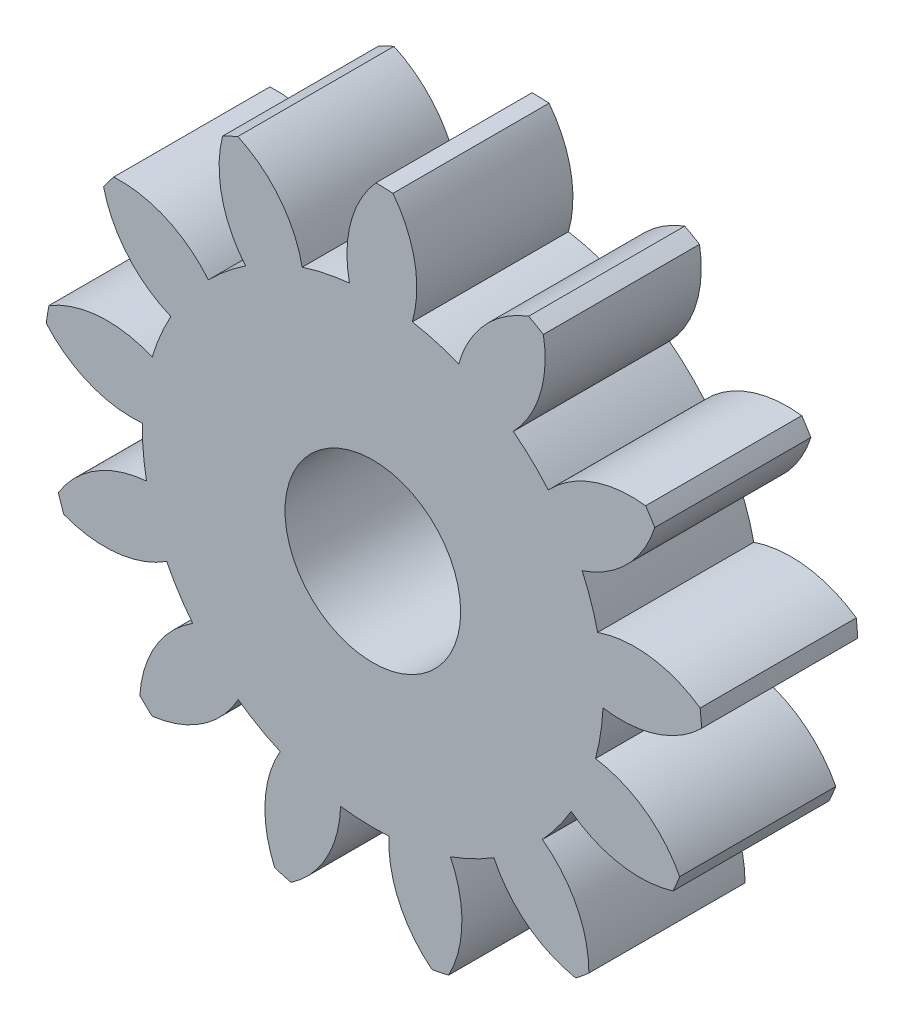
SolidWorks part; units mm, degrees
ref_plane "Front Plane" through (0, 0, 0) normal (0, 0, 1) x (1, 0, 0)
ref_plane "Top Plane" through (0, 0, 0) normal (0, 1, 0) x (1, 0, 0)
ref_plane "Right Plane" through (0, 0, 0) normal (1, 0, 0) x (0, 0, -1)
sketch "Sketch1" plane through (0, 0, 0) normal (0, 0, 1) x (1, 0, 0)
  circle A0 centre (0, 0) radius 2.25
  circle A1 centre (0, 0) radius 9.5
  dimension "D1" = 4.5
  dimension "D2" = 19
extrude "Boss-Extrude1" add sketch "Sketch1" along normal blind 4
sketch "Sketch2" plane through (0, 0, 4) normal (0, 0, 1) x (1, 0, 0)
  circle A0 centre (0, 0) radius 9.5 construction
  circle A1 centre (0, 0) radius 9.5
  arc A52 (5.3624, 2.4732) -> (7.2234, 4.3606) centre (4.4361, 5.2477) ccw
  arc A53 (7.2234, 4.3606) -> (6.9888, 4.7273) centre (0, 0) ccw
  arc A54 (6.9888, 4.7273) -> (4.4948, 3.8299) centre (6.6247, 1.8251) ccw
  arc A55 (4.4948, 3.8299) -> (3.5988, 4.682) centre (0, 0) ccw
  arc A56 (3.5988, 4.682) -> (4.3695, 7.218) centre (1.4893, 6.7082) ccw
  arc A57 (4.3695, 7.218) -> (3.9914, 7.4337) centre (0, 0) ccw
  arc A58 (3.9914, 7.4337) -> (2.2001, 5.4801) centre (5.0177, 4.6947) ccw
  arc A59 (2.2001, 5.4801) -> (1.0108, 5.8181) centre (0, 0) ccw
  arc A60 (1.0108, 5.8181) -> (0.5147, 8.4218) centre (-1.7988, 6.6319) ccw
  arc A61 (0.5147, 8.4218) -> (0.0796, 8.4371) centre (0, 0) ccw
  arc A62 (0.0796, 8.4371) -> (-0.5986, 5.8748) centre (2.2612, 6.4888) ccw
  arc A63 (-0.5986, 5.8748) -> (-1.8088, 5.6214) centre (0, 0) ccw
  arc A64 (-1.8088, 5.6214) -> (-3.4581, 7.6963) centre (-4.6747, 5.0363) ccw
  arc A65 (-3.4581, 7.6963) -> (-3.8505, 7.5077) centre (0, 0) ccw
  arc A66 (-3.8505, 7.5077) -> (-3.2602, 4.9237) centre (-1.0133, 6.7964) ccw
  arc A67 (-3.2602, 4.9237) -> (-4.214, 4.1369) centre (0, 0) ccw
  arc A68 (-4.214, 4.1369) -> (-6.6386, 5.2077) centre (-6.4798, 2.287) ccw
  arc A69 (-6.6386, 5.2077) -> (-6.8984, 4.8583) centre (0, 0) ccw
  arc A70 (-6.8984, 4.8583) -> (-5.1749, 2.8446) centre (-4.0556, 5.547) ccw
  arc A71 (-5.1749, 2.8446) -> (-5.6539, 1.7047) centre (0, 0) ccw
  arc A72 (-5.6539, 1.7047) -> (-8.2983, 1.526) centre (-6.8004, -0.9863) ccw
  arc A73 (-8.2983, 1.526) -> (-8.366, 1.096) centre (0, 0) ccw
  arc A74 (-8.366, 1.096) -> (-5.9042, 0.1139) centre (-6.1689, 3.0269) ccw
  arc A75 (-5.9042, 0.1139) -> (-5.7984, -1.1181) centre (0, 0) ccw
  arc A76 (-5.7984, -1.1181) -> (-8.057, -2.5052) centre (-5.5631, -4.0336) ccw
  arc A77 (-8.057, -2.5052) -> (-7.9171, -2.9174) centre (0, 0) ccw
  arc A78 (-7.9171, -2.9174) -> (-5.2808, -2.6429) centre (-6.869, -0.1867) ccw
  arc A79 (-5.2808, -2.6429) -> (-4.6147, -3.6847) centre (0, 0) ccw
  arc A80 (-4.6147, -3.6847) -> (-5.9699, -5.9625) centre (-3.0514, -6.1568) ccw
  arc A81 (-5.9699, -5.9625) -> (-5.6544, -6.2625) centre (0, 0) ccw
  arc A82 (-5.6544, -6.2625) -> (-3.4477, -4.7943) centre (-5.9954, -3.3574) ccw
  arc A83 (-3.4477, -4.7943) -> (-2.3737, -5.4072) centre (0, 0) ccw
  arc A84 (-2.3737, -5.4072) -> (-2.5152, -8.0539) centre (0.1594, -6.8697) ccw
  arc A85 (-2.5152, -8.0539) -> (-2.0964, -8.1729) centre (0, 0) ccw
  arc A86 (-2.0964, -8.1729) -> (-0.8247, -5.8474) centre (-3.7484, -5.7591) ccw
  arc A87 (-0.8247, -5.8474) -> (0.411, -5.8909) centre (0, 0) ccw
  arc A88 (0.411, -5.8909) -> (1.5158, -8.3002) centre (3.3336, -6.0087) ccw
  arc A89 (1.5158, -8.3002) -> (1.9419, -8.211) centre (0, 0) ccw
  arc A90 (1.9419, -8.211) -> (1.9871, -5.5609) centre (-0.6427, -6.8414) ccw
  arc A91 (1.9871, -5.5609) -> (3.1016, -5.0252) centre (0, 0) ccw
  arc A92 (3.1016, -5.0252) -> (5.1995, -6.6451) centre (5.7441, -3.7712) ccw
  arc A93 (5.1995, -6.6451) -> (5.5353, -6.3681) centre (0, 0) ccw
  arc A94 (5.5353, -6.3681) -> (4.3438, -4.0004) centre (2.6103, -6.3564) ccw
  arc A95 (4.3438, -4.0004) -> (5.0816, -3.0082) centre (0, 0) ccw
  arc A96 (5.0816, -3.0082) -> (7.692, -3.4676) centre (6.8388, -0.6698) ccw
  arc A97 (7.692, -3.4676) -> (7.8606, -3.0663) centre (0, 0) ccw
  arc A98 (7.8606, -3.0663) -> (5.7053, -1.5235) centre (5.2653, -4.4153) ccw
  arc A99 (5.7053, -1.5235) -> (5.8975, -0.3021) centre (0, 0) ccw
  arc A100 (5.8975, -0.3021) -> (8.4224, 0.5042) centre (6.3667, 2.585) ccw
  arc A101 (8.4224, 0.5042) -> (8.3852, 0.938) centre (0, 0) ccw
  arc A102 (8.3852, 0.938) -> (5.7598, 1.3024) centre (6.714, -1.4626) ccw
  arc A103 (5.7598, 1.3024) -> (5.3624, 2.4732) centre (0, 0) ccw
  arc A104 (5.3624, 2.4732) -> (7.2234, 4.3606) centre (4.4361, 5.2477) ccw
  arc A105 (7.2234, 4.3606) -> (6.9888, 4.7273) centre (0, 0) ccw
  arc A106 (6.9888, 4.7273) -> (4.4948, 3.8299) centre (6.6247, 1.8251) ccw
  arc A107 (4.4948, 3.8299) -> (3.5988, 4.682) centre (0, 0) ccw
  arc A108 (3.5988, 4.682) -> (4.3695, 7.218) centre (1.4893, 6.7082) ccw
  arc A109 (4.3695, 7.218) -> (3.9914, 7.4337) centre (0, 0) ccw
  arc A110 (3.9914, 7.4337) -> (2.2001, 5.4801) centre (5.0177, 4.6947) ccw
  arc A111 (2.2001, 5.4801) -> (1.0108, 5.8181) centre (0, 0) ccw
  arc A112 (1.0108, 5.8181) -> (0.5147, 8.4218) centre (-1.7988, 6.6319) ccw
  arc A113 (0.5147, 8.4218) -> (0.0796, 8.4371) centre (0, 0) ccw
  arc A114 (0.0796, 8.4371) -> (-0.5986, 5.8748) centre (2.2612, 6.4888) ccw
  arc A115 (-0.5986, 5.8748) -> (-1.8088, 5.6214) centre (0, 0) ccw
  arc A116 (-1.8088, 5.6214) -> (-3.4581, 7.6963) centre (-4.6747, 5.0363) ccw
  arc A117 (-3.4581, 7.6963) -> (-3.8505, 7.5077) centre (0, 0) ccw
  arc A118 (-3.8505, 7.5077) -> (-3.2602, 4.9237) centre (-1.0133, 6.7964) ccw
  arc A119 (-3.2602, 4.9237) -> (-4.214, 4.1369) centre (0, 0) ccw
  arc A120 (-4.214, 4.1369) -> (-6.6386, 5.2077) centre (-6.4798, 2.287) ccw
  arc A121 (-6.6386, 5.2077) -> (-6.8984, 4.8583) centre (0, 0) ccw
  arc A122 (-6.8984, 4.8583) -> (-5.1749, 2.8446) centre (-4.0556, 5.547) ccw
  arc A123 (-5.1749, 2.8446) -> (-5.6539, 1.7047) centre (0, 0) ccw
  arc A124 (-5.6539, 1.7047) -> (-8.2983, 1.526) centre (-6.8004, -0.9863) ccw
  arc A125 (-8.2983, 1.526) -> (-8.366, 1.096) centre (0, 0) ccw
  arc A126 (-8.366, 1.096) -> (-5.9042, 0.1139) centre (-6.1689, 3.0269) ccw
  arc A127 (-5.9042, 0.1139) -> (-5.7984, -1.1181) centre (0, 0) ccw
  arc A128 (-5.7984, -1.1181) -> (-8.057, -2.5052) centre (-5.5631, -4.0336) ccw
  arc A129 (-8.057, -2.5052) -> (-7.9171, -2.9174) centre (0, 0) ccw
  arc A130 (-7.9171, -2.9174) -> (-5.2808, -2.6429) centre (-6.869, -0.1867) ccw
  arc A131 (-5.2808, -2.6429) -> (-4.6147, -3.6847) centre (0, 0) ccw
  arc A132 (-4.6147, -3.6847) -> (-5.9699, -5.9625) centre (-3.0514, -6.1568) ccw
  arc A133 (-5.9699, -5.9625) -> (-5.6544, -6.2625) centre (0, 0) ccw
  arc A134 (-5.6544, -6.2625) -> (-3.4477, -4.7943) centre (-5.9954, -3.3574) ccw
  arc A135 (-3.4477, -4.7943) -> (-2.3737, -5.4072) centre (0, 0) ccw
  arc A136 (-2.3737, -5.4072) -> (-2.5152, -8.0539) centre (0.1594, -6.8697) ccw
  arc A137 (-2.5152, -8.0539) -> (-2.0964, -8.1729) centre (0, 0) ccw
  arc A138 (-2.0964, -8.1729) -> (-0.8247, -5.8474) centre (-3.7484, -5.7591) ccw
  arc A139 (-0.8247, -5.8474) -> (0.411, -5.8909) centre (0, 0) ccw
  arc A140 (0.411, -5.8909) -> (1.5158, -8.3002) centre (3.3336, -6.0087) ccw
  arc A141 (1.5158, -8.3002) -> (1.9419, -8.211) centre (0, 0) ccw
  arc A142 (1.9419, -8.211) -> (1.9871, -5.5609) centre (-0.6427, -6.8414) ccw
  arc A143 (1.9871, -5.5609) -> (3.1016, -5.0252) centre (0, 0) ccw
  arc A144 (3.1016, -5.0252) -> (5.1995, -6.6451) centre (5.7441, -3.7712) ccw
  arc A145 (5.1995, -6.6451) -> (5.5353, -6.3681) centre (0, 0) ccw
  arc A146 (5.5353, -6.3681) -> (4.3438, -4.0004) centre (2.6103, -6.3564) ccw
  arc A147 (4.3438, -4.0004) -> (5.0816, -3.0082) centre (0, 0) ccw
  arc A148 (5.0816, -3.0082) -> (7.692, -3.4676) centre (6.8388, -0.6698) ccw
  arc A149 (7.692, -3.4676) -> (7.8606, -3.0663) centre (0, 0) ccw
  arc A150 (7.8606, -3.0663) -> (5.7053, -1.5235) centre (5.2653, -4.4153) ccw
  arc A151 (5.7053, -1.5235) -> (5.8975, -0.3021) centre (0, 0) ccw
  arc A152 (5.8975, -0.3021) -> (8.4224, 0.5042) centre (6.3667, 2.585) ccw
  arc A153 (8.4224, 0.5042) -> (8.3852, 0.938) centre (0, 0) ccw
  arc A154 (8.3852, 0.938) -> (5.7598, 1.3024) centre (6.714, -1.4626) ccw
  arc A155 (5.7598, 1.3024) -> (5.3624, 2.4732) centre (0, 0) ccw
  dimension "D1" = 0
extrude "Cut-Extrude1" cut sketch "Sketch2" against normal through all
